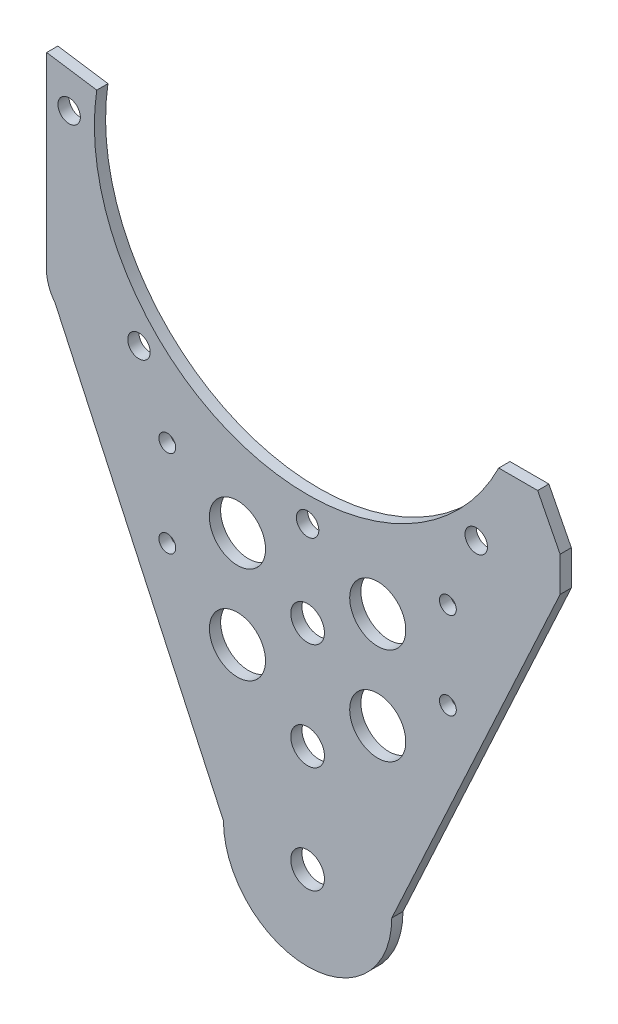
SolidWorks part; units mm, degrees
ref_plane "前视基准面" through (0, 0, 0) normal (0, 0, 1) x (1, 0, 0)
ref_plane "上视基准面" through (0, 0, 0) normal (0, 1, 0) x (1, 0, 0)
ref_plane "右视基准面" through (0, 0, 0) normal (1, 0, 0) x (0, 0, -1)
sketch "草图3" plane through (0, 0, 0) normal (0, 0, 1) x (1, 0, 0)
  line L7 (0, -1.82) -> (0, 56) construction
  line L12 (-25, -1.9902) -> (0, -20.82) construction
  line L38 (-46.5, 63) -> (-37.5766, 61.6567)
  line L102 (-46.5, 63) -> (-46.5, 28.7735)
  line L105 (34.0612, 39.1525) -> (41, 39.1525)
  line L111 (-25, 13.5098) -> (0, -1.82) construction
  line L116 (-45, 25.1098) -> (-15, -39.82)
  line L149 (45, 25.1098) -> (15, -39.82)
  line L150 (45, 25.1098) -> (45, 31.3171)
  line L151 (-25, 13.5098) -> (-25, -1.9902) construction
  line L155 (-15, -39.82) -> (-25, -39.82) construction
  line L194 (45, 31.3171) -> (41, 39.1525)
  line L196 (-25, -1.9902) -> (-25, -11.9902) construction
  arc A12 (-37.5766, 61.6567) -> (34.0612, 39.1525) centre (0, 56) ccw
  circle A16 centre (0, -1.82) radius 3
  circle A17 centre (0, 13.5) radius 2
  circle A18 centre (-30.052, 25.948) radius 2
  circle A19 centre (-42.5, 56) radius 2
  circle A24 centre (30.052, 25.948) radius 2
  circle A25 centre (-30.052, 86.052) radius 2 [skipped]
  circle A26 centre (0, 98.5) radius 2 [skipped]
  circle A27 centre (30.052, 86.052) radius 2 [skipped]
  circle A28 centre (42.5, 56) radius 2 [skipped]
  circle A29 centre (0, -20.82) radius 3
  circle A30 centre (0, -39.82) radius 3
  arc A32 (-15, -39.82) -> (15, -39.82) centre (0, -39.82) ccw
  circle A33 centre (-25, -1.9902) radius 1.5
  circle A35 centre (-25, 13.5098) radius 1.5
  circle A36 centre (25, 13.5098) radius 1.5
  circle A38 centre (25, -1.9902) radius 1.5
  circle A39 centre (-12.5, -11.4051) radius 5
  circle A40 centre (-12.5, 5.8449) radius 5
  circle A41 centre (12.5, 5.8449) radius 5
  circle A42 centre (12.5, -11.4051) radius 5
  circle A43 centre (0, 56) radius 42.5 construction
  spline S0 degree 2 poles (-45, 25.1098) (-46.2742, 26.7251) (-46.5, 28.7735) knots 0 0 0 1 1 1
extrude "凸台-拉伸1" add sketch "草图3" along normal blind 2
sketch "草图5" plane through (0, 0, 0) normal (0, 0, -1) x (-1, 0, 0)
  line L0 (0, 0.18) -> (0, 5.18)
  line L1 (0, 5.18) -> (-15, 5.18)
  line L2 (-15, 5.18) -> (-15, -9.82)
  point P0 (0, -1.82)
